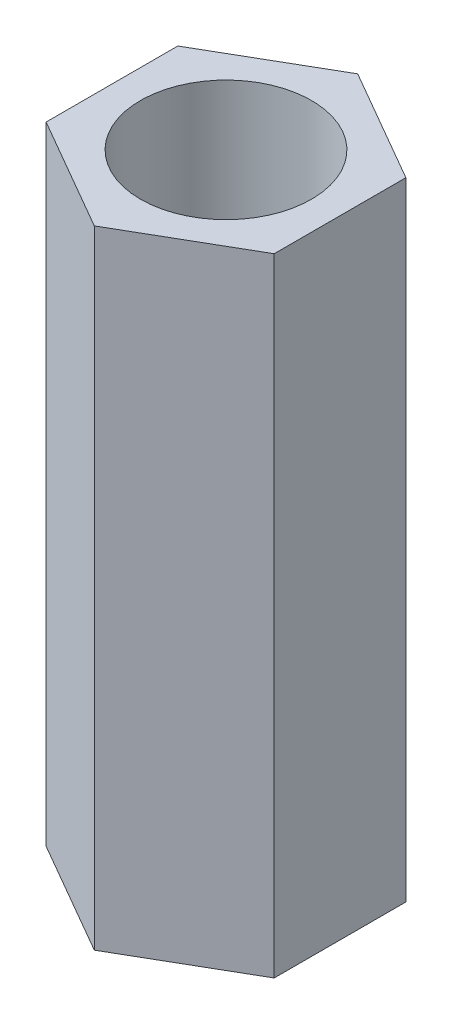
SolidWorks part; units mm, degrees
material "黄铜"
ref_plane "Front" through (0, 0, 0) normal (0, 0, 1) x (1, 0, 0)
ref_plane "Top" through (0, 0, 0) normal (0, 1, 0) x (1, 0, 0)
ref_plane "Right" through (0, 0, 0) normal (1, 0, 0) x (0, 0, -1)
sketch "草图1" plane through (0, 0, 0) normal (0, 1, 0) x (1, 0, 0)
  line L1 (0, 2.3094) -> (-2, 1.1547)
  line L2 (-2, 1.1547) -> (-2, -1.1547)
  line L3 (-2, -1.1547) -> (0, -2.3094)
  line L4 (0, -2.3094) -> (2, -1.1547)
  line L5 (2, -1.1547) -> (2, 1.1547)
  line L6 (2, 1.1547) -> (0, 2.3094)
  circle A0 centre (0, 0) radius 2 construction
  circle A1 centre (0, 0) radius 1.5
  dimension "D1" = 3
  dimension "D2" = 4
extrude "凸台-拉伸1" add sketch "草图1" along normal blind 11
